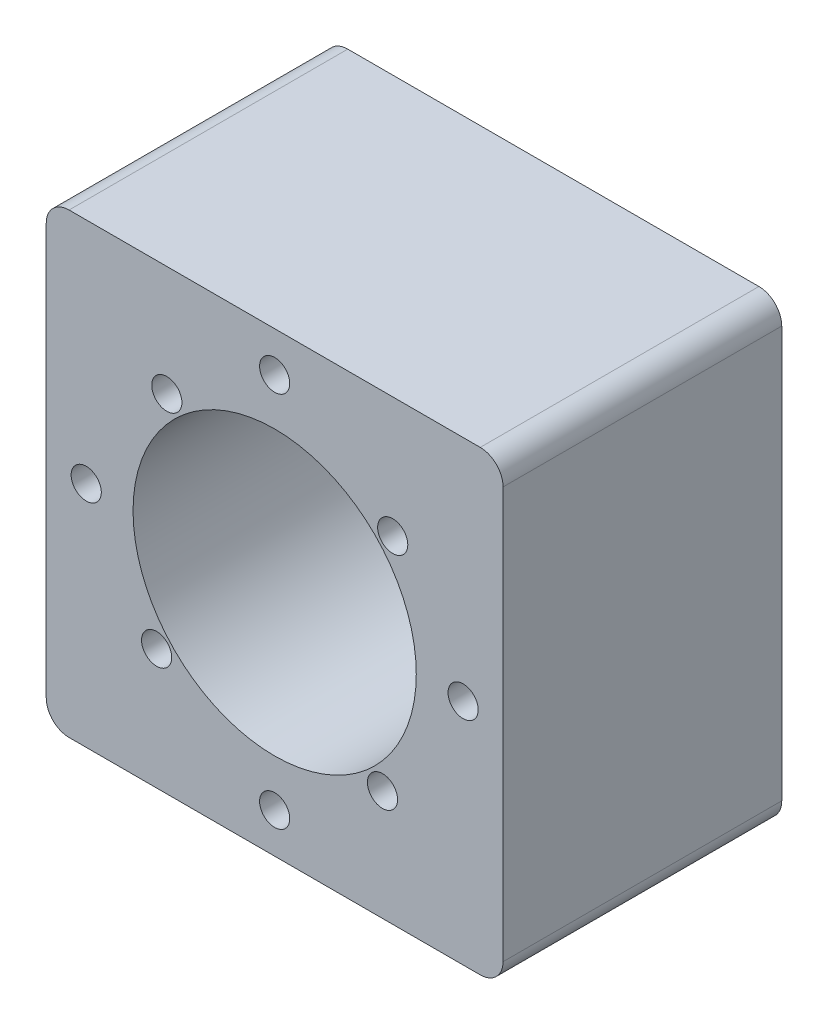
SolidWorks part; units mm, degrees
ref_plane "Plan de face" through (0, 0, 0) normal (0, 0, 1) x (1, 0, 0)
ref_plane "Plan de dessus" through (0, 0, 0) normal (0, 1, 0) x (1, 0, 0)
ref_plane "Plan de droite" through (0, 0, 0) normal (1, 0, 0) x (0, 0, -1)
sketch "Esquisse1" plane through (0, 0, 0) normal (0, 0, 1) x (1, 0, 0)
  circle A0 centre (0, 0) radius 50
  dimension "D1" = 100
extrude "Boss.-Extru.1" add sketch "Esquisse1" along normal blind 61
sketch "Esquisse2" plane through (0, 0, 0) normal (0, 0, -1) x (-1, 0, 0)
  circle A0 centre (0, 0) radius 31
  dimension "D1" = 62
extrude "Enlèv. mat.-Extru.1" cut sketch "Esquisse2" against normal blind 72
sketch "Esquisse3" plane through (0, 0, 19) normal (0, 0, -1) x (-1, 0, 0)
  circle A0 centre (0, 0) radius 30
  dimension "D1" = 60
sketch "Esquisse8" plane through (0, 0, 0) normal (0, 0, -1) x (-1, 0, 0)
  circle A2 centre (0, 0) radius 41.25
  circle A3 centre (0, 0) radius 41.25 construction
  dimension "D1" = 8.75
hole_wizard "Chambrage pour vis à tête ronde bombée M61" positions "Esquisse12" profile "Esquisse11" counterbore size "M6" standard "Ansi Metric" end condition through all
sketch "Esquisse12" plane through (0, 0, 0) normal (0, 0, -1) x (-1, 0, 0)
  circle A0 centre (0, 0) radius 41.25 construction
  point P0 (41.25, 0)
  point P4 (0, 41.25)
  point P6 (-41.25, 0)
  point P8 (0, -41.25)
sketch "Esquisse11" plane through (-41.25, 0, 0) normal (1, 0, 0) x (0, 1, 0)
  line L0 (0, 0) -> (0, 61)
  line L1 (0, 61) -> (3.3, 61)
  line L3 (3.3, 61) -> (3.3, 4.6)
  line L4 (3.3, 4.6) -> (6.5, 4.6)
  line L5 (6.5, 4.6) -> (6.5, 0)
  line L7 (6.5, 0) -> (0, 0)
  line L11 (0, -6.35) -> (0, 107.95) construction
  dimension "Diamètre du perçage jusqu'au prochain" = 6.6
  dimension "Profondeur du perçage jusqu'au prochain" = 61
  dimension "Diamètre du chambrage" = 13
  dimension "Profondeur du chambrage" = 4.6
hole_wizard "Dégagement M61" positions "Esquisse18" profile "Esquisse19" hole size "M6" standard "JIS"
sketch "Esquisse18" plane through (0, 0, 61) normal (0, 0, 1) x (1, 0, 0)
  point P0 (-23.6086, 25.8386)
  point P2 (-25.8386, -23.6086)
  point P4 (23.6086, -25.8386)
  point P6 (25.8386, 23.6086)
sketch "Esquisse19" plane through (-23.6086, 25.8386, 61) normal (1, 0, 0) x (0, -1, 0)
  line L0 (0, 0) -> (0, 6.9053)
  line L1 (0, 6.9053) -> (3.3, 5)
  line L2 (3.3, 5) -> (3.3, 0)
  line L5 (3.3, 0) -> (0, 0)
  line L10 (0, 6.9053) -> (-3.3, 5) construction
  line L11 (0, -6.35) -> (0, 107.95) construction
  dimension "Diamètre du perçage" = 6.6
  dimension "Profondeur du perçage" = 5
  dimension "Angle de pointe" = 120
sketch "Esquisse20" plane through (0, 0, 0) normal (0, 0, -1) x (-1, 0, 0)
  line L1 (-45, -50) -> (45, -50)
  line L2 (-50, -45) -> (-50, 45)
  line L3 (-45, 50) -> (45, 50)
  line L4 (50, -45) -> (50, 45)
  line L5 (-50, -50) -> (50, 50) construction
  line L6 (-50, 50) -> (50, -50) construction
  circle A0 centre (0, 0) radius 50 construction
  arc A1 (-45, -50) -> (-50, -45) centre (-45, -45) cw
  arc A2 (45, -50) -> (50, -45) centre (45, -45) ccw
  arc A3 (50, 45) -> (45, 50) centre (45, 45) ccw
  arc A4 (-50, 45) -> (-45, 50) centre (-45, 45) cw
  point P0 (0, 0)
  circle M9 centre (0, 0) radius 50
  dimension "D1" = 5
extrude "Boss.-Extru.2" add sketch "Esquisse20" against normal offset from surface (61 mm away) 61 contours L3 L2 M9 | L4 L3 M9 | L1 L4 M9 | L2 L1 M9
sketch "Esquisse23" plane through (0, 0, 0) normal (0, 0, -1) x (-1, 0, 0)
  circle A0 centre (0, 0) radius 31
  circle A1 centre (0, 0) radius 25
  dimension "D1" = 50
extrude "Boss.-Extru.3" add sketch "Esquisse23" against normal blind 7
sketch "Esquisse24" plane through (0, 0, 0) normal (0, 0, -1) x (-1, 0, 0)
  circle A0 centre (0, 0) radius 31
  dimension "D1" = 62
extrude "Enlèv. mat.-Extru.2" cut sketch "Esquisse24" against normal blind 3
